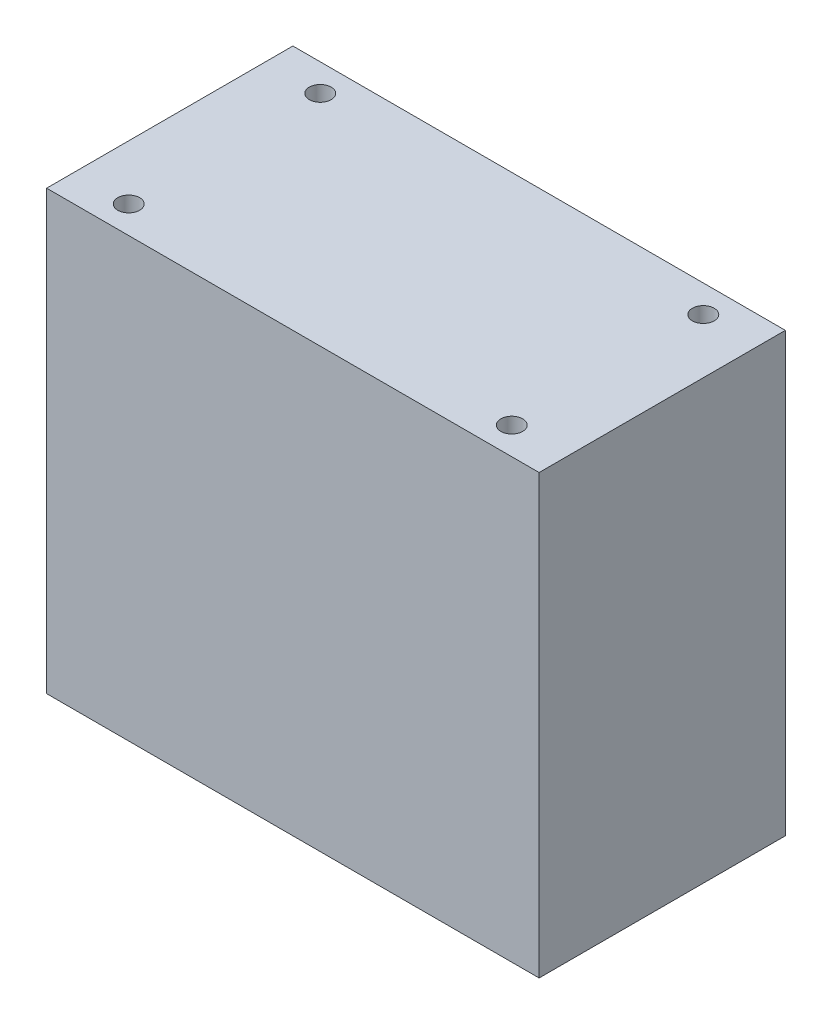
SolidWorks part; units mm, degrees
material "2.0060 (Cu-ETP)"
ref_plane "前视基准面" through (0, 0, 0) normal (0, 0, 1) x (1, 0, 0)
ref_plane "上视基准面" through (0, 0, 0) normal (0, 1, 0) x (1, 0, 0)
ref_plane "右视基准面" through (0, 0, 0) normal (1, 0, 0) x (0, 0, -1)
sketch "草图1" plane through (0, 0, 0) normal (0, 1, 0) x (1, 0, 0)
  line L1 (-45, 22.5) -> (45, 22.5)
  line L2 (-45, 22.5) -> (-45, -22.5)
  line L3 (-45, -22.5) -> (45, -22.5)
  line L4 (45, 22.5) -> (45, -22.5)
  line L5 (-45, 22.5) -> (45, -22.5) construction
  line L6 (-45, -22.5) -> (45, 22.5) construction
  line L7 (-35, 17.5) -> (35, 17.5)
  line L8 (-35, 17.5) -> (-35, -17.5)
  line L9 (-35, -17.5) -> (35, -17.5)
  line L10 (35, 17.5) -> (35, -17.5)
  line L11 (-35, 17.5) -> (35, -17.5) construction
  line L12 (-35, -17.5) -> (35, 17.5) construction
  circle A0 centre (-35, 17.5) radius 2
  circle A1 centre (-35, -17.5) radius 2
  circle A2 centre (35, -17.5) radius 2
  circle A3 centre (35, 17.5) radius 2
  point P0 (0, 0)
  point P5 (0, 0)
  dimension "D1" = 90
  dimension "D2" = 45
  dimension "D3" = 70
  dimension "D4" = 35
extrude "凸台-拉伸1" add sketch "草图1" along normal blind 80 contours L4 L1 L2 L3 A3 L10 A2 L9 A1 L8 A0 L7 | A3 L7 A0 L8 A1 L9 A2 L10
